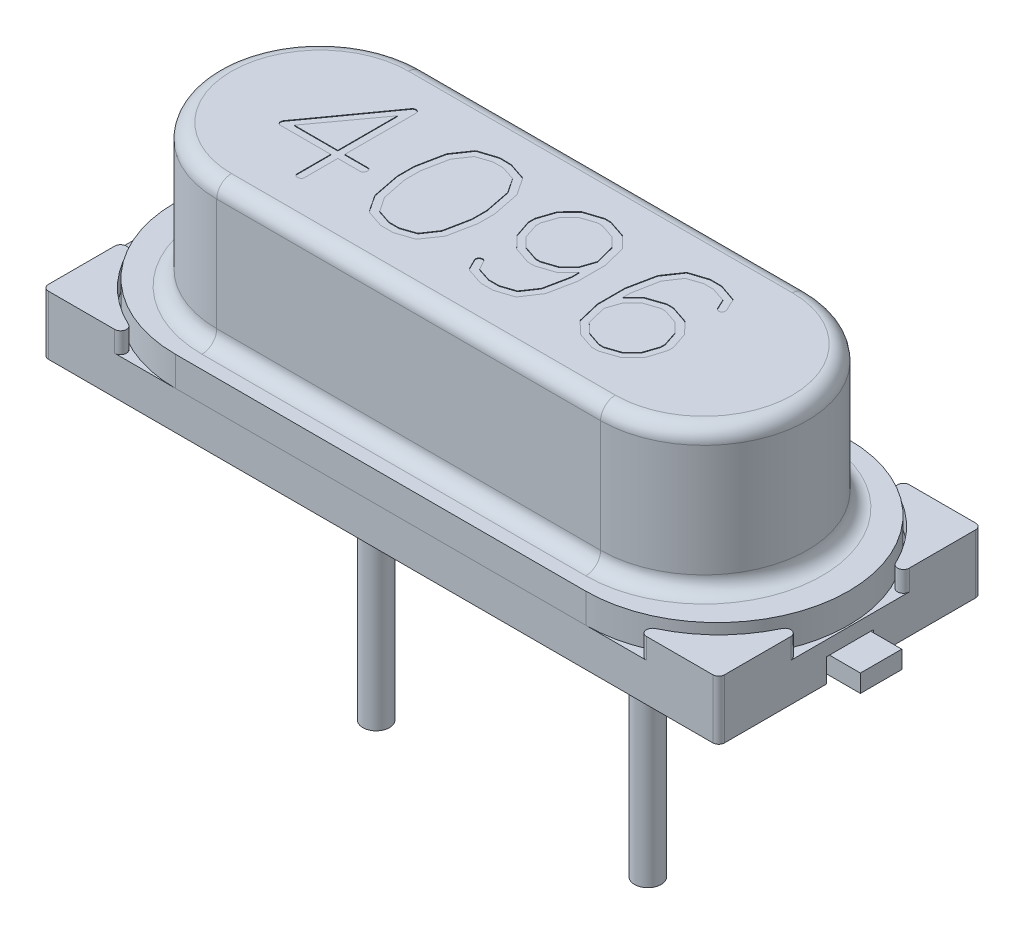
SolidWorks part; units mm, degrees
ref_plane "Front Plane" through (0, 0, 0) normal (0, 0, 1) x (1, 0, 0)
ref_plane "Top Plane" through (0, 0, 0) normal (0, 1, 0) x (1, 0, 0)
ref_plane "Right Plane" through (0, 0, 0) normal (1, 0, 0) x (0, 0, -1)
sketch "Sketch1" plane through (0, 0, 0) normal (0, 1, 0) x (1, 0, 0)
  line L1 (-5.725, 2.225) -> (5.725, 2.225)
  line L2 (-5.725, 2.225) -> (-5.725, -2.225)
  line L3 (-5.725, -2.225) -> (5.725, -2.225)
  line L4 (5.725, 2.225) -> (5.725, -2.225)
  line L5 (-5.725, 2.225) -> (5.725, -2.225) construction
  line L6 (-5.725, -2.225) -> (5.725, 2.225) construction
  point P0 (0, 0)
  dimension "D1" = 11.45
  dimension "D2" = 4.45
extrude "Boss-Extrude1" add sketch "Sketch1" against normal blind 1
sketch "Sketch2" plane through (0, 0, 0) normal (0, 1, 0) x (1, 0, 0)
  line L0 (-3.5, 0) -> (3.5, 0) construction
  line L1 (-3.5, 2.25) -> (3.5, 2.25)
  line L2 (-3.5, -2.25) -> (3.5, -2.25)
  line L3 (5.75, 0) -> (5.75, 5.2042) construction
  line L4 (-5.75, 0) -> (-5.75, 5.2042) construction
  arc A0 (-3.5, 2.25) -> (-3.5, -2.25) centre (-3.5, 0) ccw
  arc A1 (3.5, -2.25) -> (3.5, 2.25) centre (3.5, 0) ccw
  point P2 (0, 0)
  dimension "D1" = 4.5
  dimension "D2" = 11.5
extrude "Cut-Extrude2" cut sketch "Sketch2" against normal blind 0.35
fillet "Fillet1" radius 0.1 12 edges at (-5.725, -0.5, 2.225) (-5.725, -0.5, -2.225) (5.725, -0.5, -2.225) (5.725, -0.5, 2.225) (3.8345, -0.175, 2.225) (5.725, -0.175, -0.3345) (5.725, -0.175, 0.3345) (3.8345, -0.175, -2.225) (-3.8345, -0.175, -2.225) (-5.725, -0.175, 0.3345) (-5.725, -0.175, -0.3345) (-3.8345, -0.175, 2.225)
sketch "Sketch3" plane through (0, -0.35, 0) normal (0, 1, 0) x (1, 0, 0)
  line L0 (-3.475, 0) -> (3.475, 0) construction
  line L1 (-3.475, 2.225) -> (3.475, 2.225)
  line L2 (-3.475, -2.225) -> (3.475, -2.225)
  line L3 (5.7, 0) -> (5.7, 3.6957) construction
  line L4 (-5.7, 0) -> (-5.7, 3.6957) construction
  arc A0 (-3.475, 2.225) -> (-3.475, -2.225) centre (-3.475, 0) ccw
  arc A1 (3.475, -2.225) -> (3.475, 2.225) centre (3.475, 0) ccw
  point P2 (0, 0)
  dimension "D1" = 11.4
  dimension "D2" = 4.45
extrude "Boss-Extrude2" add sketch "Sketch3" along normal blind 0.5 separate body
sketch "Sketch4" plane through (0, 0.15, 0) normal (0, 1, 0) x (1, 0, 0)
  line L2 (-3.25, 0) -> (3.25, 0) construction
  line L3 (-3.25, 1.75) -> (3.25, 1.75)
  line L4 (-3.25, -1.75) -> (3.25, -1.75)
  line L5 (5, 0) -> (-5, 0) construction
  arc A2 (-3.25, 1.75) -> (-3.25, -1.75) centre (-3.25, 0) ccw
  arc A3 (3.25, -1.75) -> (3.25, 1.75) centre (3.25, 0) ccw
  point P2 (0, 0)
  dimension "D1" = 3.5
  dimension "D2" = 10
extrude "Boss-Extrude3" add sketch "Sketch4" along normal blind 2.4
fillet "Fillet2" radius 0.25 8 edges at (-5, 0.15, 0) (0, 0.15, -1.75) (5, 0.15, 0) (-5, 2.55, 0) (0, 2.55, -1.75) (5, 2.55, 0) (0, 0.15, 1.75) (0, 2.55, 1.75)
sketch "Sketch5" plane through (0, 2.55, 0) normal (0, 1, 0) x (1, 0, 0)
  line L0 (-4.4108, -0.95) -> (4.4108, -0.95) construction
  line L1 (3.25, 1.75) -> (-3.25, 1.75) construction
  arc A0 (-3.25, 1.5) -> (-3.25, -1.5) centre (-3.25, 0) ccw construction
  arc A1 (3.25, -1.5) -> (3.25, 1.5) centre (3.25, 0) ccw construction
  text T0 "4096\r\n" font "SWSimp" height 2
  dimension "D1" = 2.7
extrude "Cut-Extrude3" cut sketch "Sketch5" against normal blind 0.01
sketch "Sketch6" plane through (0, -1, 0) normal (0, -1, 0) x (1, 0, 0)
  line L0 (0, 3.2884) -> (0, -3.5226) construction
  line L1 (0, 0) -> (-6.0373, 0) construction
  line L2 (-2.2, 0.4) -> (-7.8383, 0.4)
  line L3 (-2.2, 0.4) -> (-2.2, -0.4)
  line L4 (-2.2, -0.4) -> (-7.8383, -0.4)
  line L5 (-7.8383, 0.4) -> (-7.8383, -0.4)
  line L6 (2.2, -0.4) -> (7.8383, -0.4)
  line L7 (7.8383, 0.4) -> (7.8383, -0.4)
  line L8 (2.2, 0.4) -> (7.8383, 0.4)
  line L9 (2.2, 0.4) -> (2.2, -0.4)
  dimension "D1" = 4.4
  dimension "D2" = 0.8
extrude "Cut-Extrude4" cut sketch "Sketch6" against normal blind 0.4
sketch "Sketch7" plane through (0, -0.6, 0) normal (0, -1, 0) x (1, 0, 0)
  line L4 (5.675, 0.35) -> (6.25, 0.35)
  line L5 (6.25, 0.35) -> (6.25, -0.35)
  line L6 (6.25, -0.35) -> (5.675, -0.35)
  line L7 (0, 3.4984) -> (0, -3.58) construction
  line L8 (5.675, 0.35) -> (2.25, 0.35)
  line L9 (2.25, 0.35) -> (2.25, -0.35)
  line L10 (2.25, -0.35) -> (5.675, -0.35)
  line L11 (5.675, -0.35) -> (5.675, 0.35)
  line L12 (5.675, 0.35) -> (2.25, 0.35)
  line L13 (2.25, 0.35) -> (2.25, -0.35)
  line L14 (2.25, -0.35) -> (5.675, -0.35)
  line L16 (-5.675, 0.35) -> (-6.25, 0.35)
  line L17 (-6.25, 0.35) -> (-6.25, -0.35)
  line L18 (-6.25, -0.35) -> (-5.675, -0.35)
  line L19 (-2.25, -0.35) -> (-5.675, -0.35)
  line L20 (-2.25, 0.35) -> (-2.25, -0.35)
  line L21 (-5.675, 0.35) -> (-2.25, 0.35)
  dimension "D2" = 12.5
  dimension "D1" = 0.05
extrude "Boss-Extrude4" add sketch "Sketch7" along normal blind 0.3 separate body
sketch "Sketch8" plane through (0, -0.35, 0) normal (0, -1, 0) x (1, 0, 0)
  line L0 (0, 3.4464) -> (0, -3.9228) construction
  circle A0 centre (2.3, 0) radius 0.825
  circle A1 centre (-2.3, 0) radius 0.825
  point P5 (0, 0)
  dimension "D2" = 1.65
  dimension "D1" = 4.6
extrude "Cut-Extrude5" cut sketch "Sketch8" against normal blind 0.01
sketch "Sketch9" plane through (0, -0.34, 0) normal (0, -1, 0) x (1, 0, 0)
  line L0 (0, 2.6355) -> (0, -3.1631) construction
  circle A0 centre (2.3, 0) radius 0.225
  circle A1 centre (-2.3, 0) radius 0.225
  dimension "D1" = 0.45
extrude "Boss-Extrude5" add sketch "Sketch9" along normal blind 5.4
